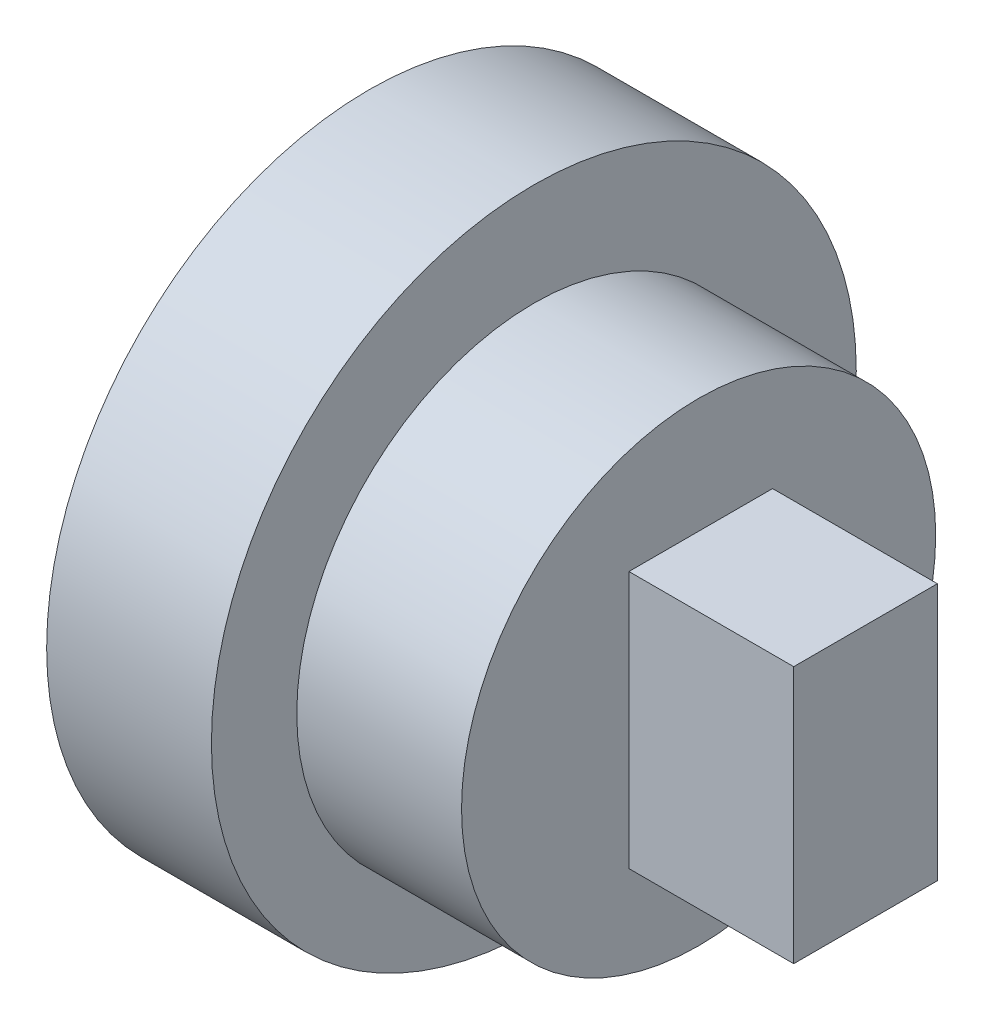
SolidWorks part; units mm, degrees
ref_plane "Front Plane" through (0, 0, 0) normal (0, 0, 1) x (1, 0, 0)
ref_plane "Top Plane" through (0, 0, 0) normal (0, 1, 0) x (1, 0, 0)
ref_plane "Right Plane" through (0, 0, 0) normal (1, 0, 0) x (0, 0, -1)
sketch "Sketch1" plane through (0, 0, 0) normal (1, 0, 0) x (0, 0, -1)
  circle A0 centre (0, 1.042) radius 19.5674
extrude "Boss-Extrude1" add sketch "Sketch1" along normal blind 10
sketch "Sketch2" plane through (10, 0, 0) normal (1, 0, 0) x (0, 0, -1)
  circle A0 centre (0, 0) radius 14.3881
extrude "Boss-Extrude2" add sketch "Sketch2" along normal blind 10
sketch "Sketch3" plane through (20, 0, 0) normal (1, 0, 0) x (0, 0, -1)
  line L1 (-4.2292, 7.4005) -> (4.4882, 7.4005)
  line L2 (-4.2292, 7.4005) -> (-4.2292, -8.213)
  line L3 (-4.2292, -8.213) -> (4.4882, -8.213)
  line L4 (4.4882, 7.4005) -> (4.4882, -8.213)
extrude "Boss-Extrude3" add sketch "Sketch3" along normal blind 10
